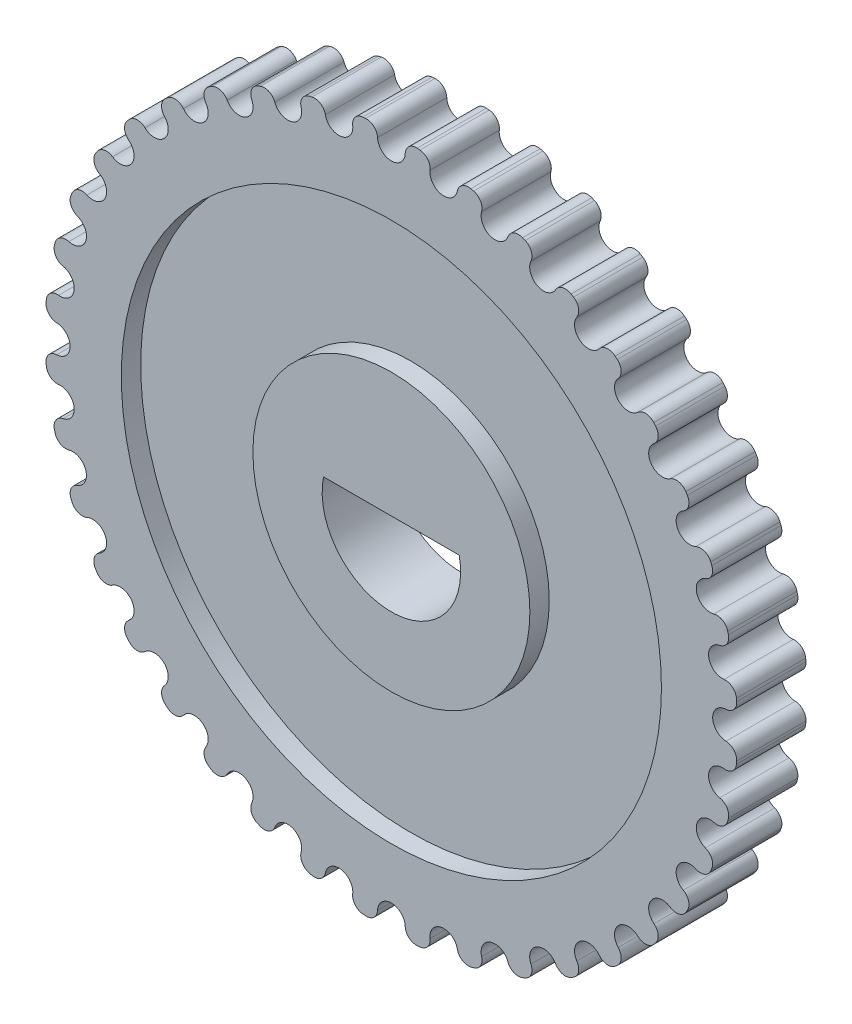
SolidWorks part; units mm, degrees
ref_plane "Front Plane" through (0, 0, 0) normal (0, 0, 1) x (1, 0, 0)
ref_plane "Top Plane" through (0, 0, 0) normal (0, 1, 0) x (1, 0, 0)
ref_plane "Right Plane" through (0, 0, 0) normal (1, 0, 0) x (0, 0, -1)
sketch "Sketch1" plane through (0, 0, 0) normal (0, 0, 1) x (1, 0, 0)
  circle A0 centre (0, 0) radius 25
  dimension "D1" = 50
extrude "Boss-Extrude1" add sketch "Sketch1" along normal mid plane 5
sketch "Sketch2" plane through (0, 0, 2.5) normal (0, 0, 1) x (1, 0, 0)
  circle A0 centre (0, 0) radius 19.5
  circle A1 centre (0, 0) radius 10
  point P5 (0, 0)
  point P6 (0, 0)
  point P7 (0, 0)
  dimension "D1" = 20
  dimension "D2" = 39
extrude "Cut-Extrude1" cut sketch "Sketch2" against normal blind 1.4
mirror "Mirror1" about plane through (0, 0, 0) normal (0, 0, 1) of "Cut-Extrude1"
sketch "Sketch3" plane through (0, 0, 2.5) normal (0, 0, 1) x (1, 0, 0)
  line L0 (0, 32.9228) -> (0, -5.4235) construction
  line L1 (-20.5396, 25) -> (18.766, 25) construction
  line L2 (-1, 24.2) -> (-1, 25.2)
  line L3 (1, 24.2) -> (1, 25.2)
  line L4 (-1, 25.2) -> (1, 25.2)
  arc A0 (-1, 24.2) -> (1, 24.2) centre (0, 24.2) ccw
  circle A3 centre (0, 0) radius 25 construction
  dimension "D1" = 2
  dimension "D2" = 0.8
  dimension "D3" = 1
extrude "Cut-Extrude2" cut sketch "Sketch3" against normal through all
fillet "Fillet1" radius 0.8 2 edges at (1, 24.98, 0) (-1, 24.98, 0)
pattern_circular "CirPattern1" count 40 over 360 about axis through (0, 0, 0) along (0, 0, 1) of "Fillet1", "Cut-Extrude2"
sketch "Sketch4" plane through (0, 0, 2.5) normal (0, 0, 1) x (1, 0, 0)
  line L0 (-4.899, 1) -> (4.899, 1)
  arc A0 (-4.899, 1) -> (4.899, 1) centre (0, 0) ccw
  point P5 (0, 0)
  dimension "D2" = 10
  dimension "D1" = 1
extrude "Cut-Extrude3" cut sketch "Sketch4" against normal through all
